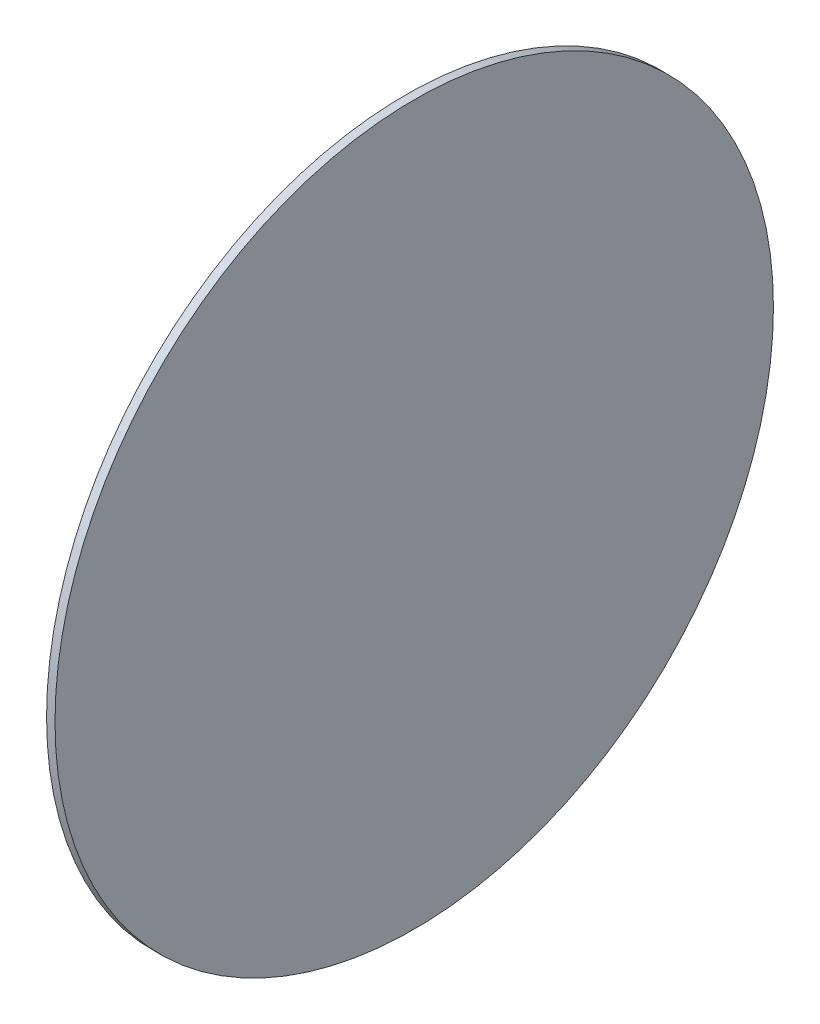
SolidWorks part; units mm, degrees
ref_plane "Front Plane" through (0, 0, 0) normal (1, 0, 0) x (0, 1, 0)
ref_plane "Top Plane" through (0, 0, 0) normal (0, 0, 1) x (0, 1, 0)
ref_plane "Right Plane" through (0, 0, 0) normal (0, 1, 0) x (-1, 0, 0)
sketch "Sketch1" plane through (0, 0, 0) normal (1, 0, 0) x (0, 1, 0)
  circle A0 centre (0, 0) radius 85.344
  circle A1 centre (0, 0) radius 52.07
  dimension "D1" = 170.688
  dimension "D2" = 104.14
extrude "Boss-Extrude1" add sketch "Sketch1" along normal blind 2.0066 contours A0
